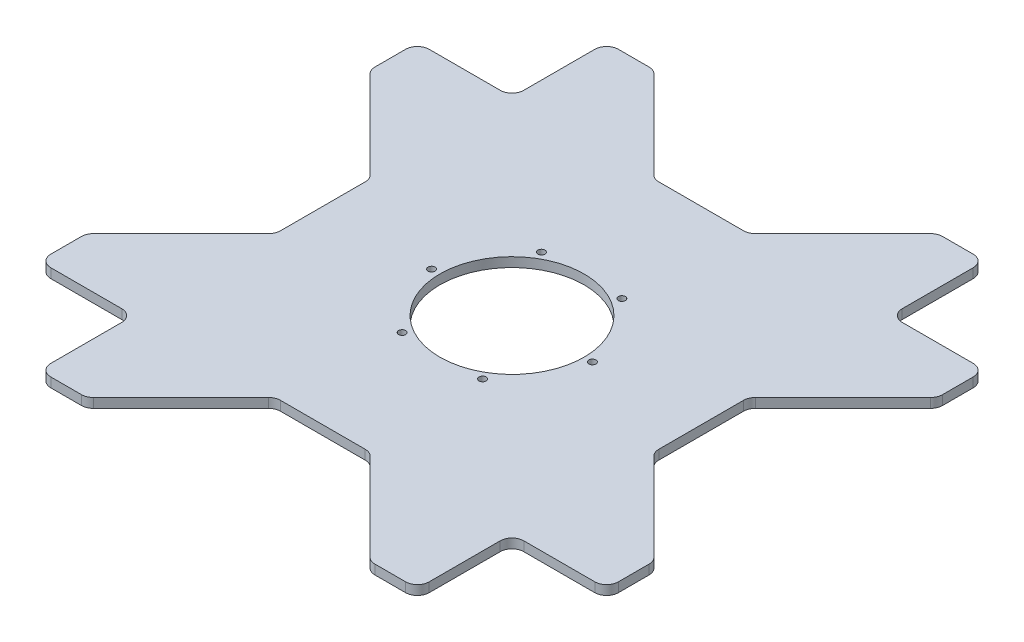
SolidWorks part; units mm, degrees
ref_plane "前视基准面" through (0, 0, 0) normal (0, 0, 1) x (1, 0, 0)
ref_plane "上视基准面" through (0, 0, 0) normal (0, 1, 0) x (1, 0, 0)
ref_plane "右视基准面" through (0, 0, 0) normal (1, 0, 0) x (0, 0, -1)
other "Configuration Table"
sketch "草图1" plane through (0, 0, 0) normal (0, 1, 0) x (1, 0, 0)
  line L1 (0, 0) -> (160, 0)
  line L2 (0, 0) -> (0, 160)
  line L3 (0, 160) -> (160, 160)
  line L4 (160, 0) -> (160, 160)
  dimension "D1" = 160
  dimension "D2" = 160
extrude "凸台-拉伸1" add sketch "草图1" along normal blind 4
sketch "草图2" plane through (0, 4, 0) normal (0, 1, 0) x (1, 0, 0)
  line L0 (0, 100) -> (-40, 140)
  line L1 (0, 160) -> (0, 0) construction
  line L2 (-40, 140) -> (-40, 160)
  line L3 (-40, 160) -> (0, 160)
  line L4 (0, 160) -> (0, 200)
  line L5 (0, 200) -> (20, 200)
  line L6 (20, 200) -> (60, 160)
  line L7 (160, 160) -> (0, 160) construction
  line L8 (60, 160) -> (0, 100)
  line L9 (-65.8007, 80) -> (246.0394, 80) construction
  line L10 (80, 215.1305) -> (80, -18.8063) construction
  line L11 (160, 0) -> (160, 160) construction
  line L12 (0, 0) -> (160, 0) construction
  line L13 (60, 0) -> (0, 60)
  line L14 (20, -40) -> (60, 0)
  line L15 (0, -40) -> (20, -40)
  line L16 (0, 0) -> (0, -40)
  line L17 (-40, 0) -> (0, 0)
  line L18 (-40, 20) -> (-40, 0)
  line L19 (0, 60) -> (-40, 20)
  line L20 (160, 60) -> (200, 20)
  line L21 (200, 20) -> (200, 0)
  line L22 (200, 0) -> (160, 0)
  line L23 (160, 0) -> (160, -40)
  line L24 (160, -40) -> (140, -40)
  line L25 (140, -40) -> (100, 0)
  line L26 (100, 0) -> (160, 60)
  line L27 (100, 160) -> (160, 100)
  line L28 (140, 200) -> (100, 160)
  line L29 (160, 200) -> (140, 200)
  line L30 (160, 160) -> (160, 200)
  line L31 (200, 160) -> (160, 160)
  line L32 (200, 140) -> (200, 160)
  line L33 (160, 100) -> (200, 140)
  dimension "D1" = 20
  dimension "D2" = 20
  dimension "D3" = 45
  dimension "D4" = 45
  dimension "D5" = 40
  dimension "D6" = 40
extrude "凸台-拉伸2" add sketch "草图2" against normal up to surface (4 mm away) up to face at (80, 0, -80)
fillet "圆角1" radius 5 28 edges at (-40, 2, -20) (-40, 2, 0) (0, 2, 0) (0, 2, 40) (20, 2, 40) (60, 2, 0) (100, 2, 0) (140, 2, 40) (160, 2, 40) (160, 2, 0) (200, 2, 0) (200, 2, -20) (160, 2, -60) (160, 2, -100) (200, 2, -140) (200, 2, -160) (160, 2, -160) (160, 2, -200) (140, 2, -200) (100, 2, -160) (60, 2, -160) (20, 2, -200) (0, 2, -200) (0, 2, -160) (-40, 2, -160) (-40, 2, -140) (0, 2, -60) (0, 2, -100)
sketch "草图3" plane through (0, 4, 0) normal (0, 1, 0) x (1, 0, 0)
  line L0 (97.9289, 160) -> (62.0711, 160) construction
  line L1 (97.9289, 160) -> (62.0711, 160) construction
  line L2 (0, 97.9289) -> (0, 62.0711) construction
  line L3 (0, 97.9289) -> (0, 62.0711) construction
  line L4 (80, 80) -> (80, 160) construction
  circle A0 centre (80, 80) radius 30.5
  circle A1 centre (97, 109.4449) radius 1.5
  circle A2 centre (114, 80) radius 1.5
  circle A3 centre (97, 50.5551) radius 1.5
  circle A4 centre (63, 50.5551) radius 1.5
  circle A5 centre (46, 80) radius 1.5
  circle A6 centre (63, 109.4449) radius 1.5
  point P5 (80, 160)
  point P8 (0, 80)
  dimension "D1" = 61
  dimension "D2" = 3
  dimension "D3" = 34
  dimension "D4" = 30
  dimension "D5" = 6
extrude "切除-拉伸1" cut sketch "草图3" against normal blind 10
